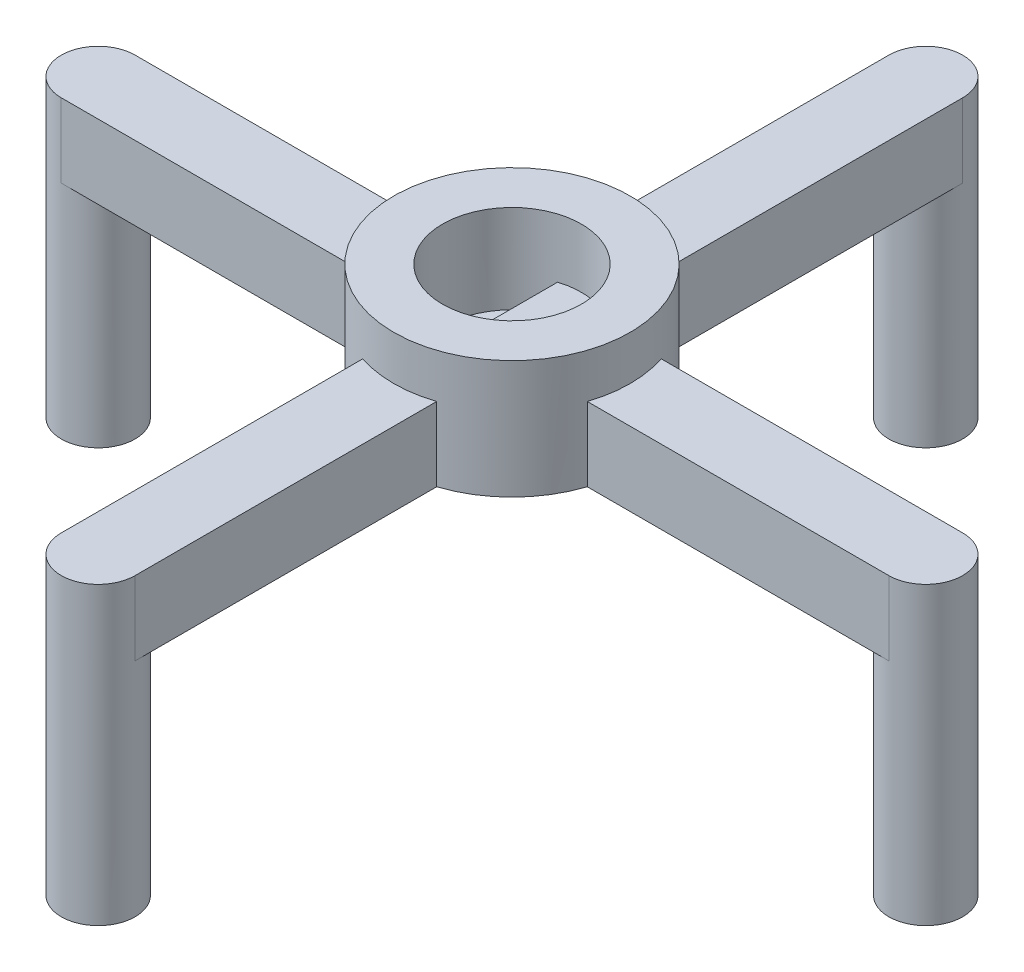
SolidWorks part; units mm, degrees
ref_plane "Front Plane" through (0, 0, 0) normal (0, 0, 1) x (1, 0, 0)
ref_plane "Top Plane" through (0, 0, 0) normal (0, 1, 0) x (1, 0, 0)
ref_plane "Right Plane" through (0, 0, 0) normal (1, 0, 0) x (0, 0, -1)
sketch "Sketch1" plane through (0, 0, 0) normal (0, 1, 0) x (1, 0, 0)
  circle A0 centre (-7, 0) radius 0.625
  circle A1 centre (7, 0) radius 0.625
  dimension "D1" = 1.25
  dimension "D2" = 1.25
  dimension "D3" = 14
  dimension "D4" = 7
extrude "Boss-Extrude1" add sketch "Sketch1" along normal blind 5
sketch "Sketch2" plane through (0, 0, 0) normal (1, 0, 0) x (0, 0, -1)
  line L0 (-0.625, 5) -> (-0.625, 0) construction
  line L1 (0.625, 5) -> (-0.625, 5)
  line L2 (0.625, 5) -> (0.625, 3.75)
  line L3 (0.625, 3.75) -> (-0.625, 3.75)
  line L4 (-0.625, 5) -> (-0.625, 3.75)
extrude "Boss-Extrude2" add sketch "Sketch2" along normal up to surface and the other way up to surface up to face at (7, 5, 0.625) other way up to face at (-7, 5, 0.625)
sketch "Sketch6" plane through (0, 0, 0) normal (0, 0, 1) x (1, 0, 0)
  line L0 (0, 0) -> (0, 1.7516) construction
pattern_circular "CirPattern4" count 2 every 90 about axis through (0, 0, 0) along (0, 1, 0) of bodies 103
sketch "Sketch7" plane through (0, 5, 0) normal (0, 1, 0) x (1, 0, 0)
  circle A1 centre (0, 0) radius 1.5
  dimension "D1" = 3
extrude "Cut-Extrude1" cut sketch "Sketch7" against normal up to surface (1.25 mm away) up to face at (0, 3.75, 0)
sketch "Sketch8" plane through (0, 3.75, 0) normal (0, -1, 0) x (1, 0, 0)
  circle A0 centre (0, 0) radius 2
  dimension "D1" = 4
extrude "Boss-Extrude4" add sketch "Sketch8" against normal blind 0.5
sketch "Sketch9" plane through (0, 4.25, 0) normal (0, 1, 0) x (1, 0, 0)
  circle A0 centre (0, 0) radius 2
  circle A1 centre (0, 0) radius 1.175
  dimension "D1" = 2.35
  dimension "D2" = 4
extrude "Boss-Extrude5" add sketch "Sketch9" along normal blind 1.5
sketch "Sketch11" plane through (0, 4.25, 0) normal (0, 1, 0) x (1, 0, 0)
  line L0 (0, 0) -> (0, 1.175) construction
  line L1 (0, 0) -> (0, -1.175) construction
  line L2 (-0.35, 0) -> (0.35, 0) construction
  line L3 (-0.35, 0) -> (-0.35, 1.1217)
  line L4 (-0.35, 0) -> (-0.35, -1.1217)
  line L5 (0.35, 1.1217) -> (0.35, -1.1217)
  circle A0 centre (0, 0) radius 1.175 construction
  circle A1 centre (0, 0) radius 1.175 construction
  arc A2 (-0.35, -1.1217) -> (0.35, -1.1217) centre (0, 0) ccw
  arc A3 (0.35, 1.1217) -> (-0.35, 1.1217) centre (0, 0) ccw
  point P10 (0, 0)
  dimension "D1" = 0.7
extrude "Boss-Extrude6" add sketch "Sketch11" along normal blind 0.5
